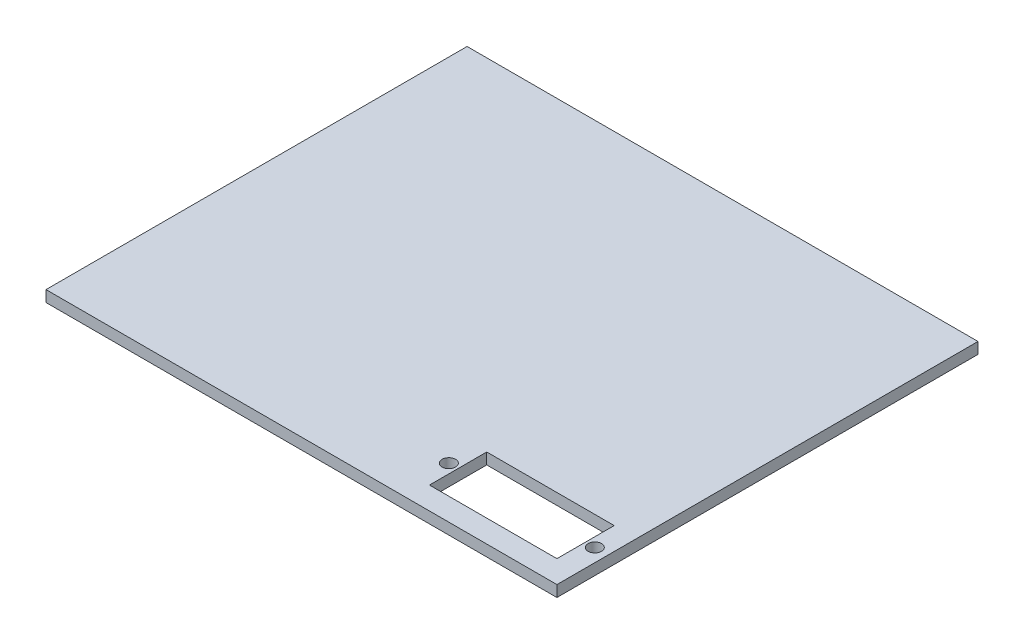
SolidWorks part; units mm, degrees
ref_plane "前视基准面" through (0, 0, 0) normal (0, 0, 1) x (1, 0, 0)
ref_plane "上视基准面" through (0, 0, 0) normal (0, 1, 0) x (1, 0, 0)
ref_plane "右视基准面" through (0, 0, 0) normal (1, 0, 0) x (0, 0, -1)
sketch "草图1" plane through (0, 0, 0) normal (0, 1, 0) x (1, 0, 0)
  line L1 (-45.5, 37.5) -> (45.5, 37.5)
  line L2 (-45.5, 37.5) -> (-45.5, -37.5)
  line L3 (-45.5, -37.5) -> (45.5, -37.5)
  line L4 (45.5, 37.5) -> (45.5, -37.5)
  line L5 (-45.5, 37.5) -> (45.5, -37.5) construction
  line L6 (-45.5, -37.5) -> (45.5, 37.5) construction
  point P0 (0, 0)
  dimension "D1" = 75
  dimension "D2" = 91
extrude "凸台-拉伸1" add sketch "草图1" along normal blind 2
ref_plane "基准面1" through (0, 2, 0) normal (0, 1, 0) x (1, 0, 0)
sketch "草图2" plane through (0, 2, 0) normal (0, 1, 0) x (1, 0, 0)
  line L0 (-45.5, -37.5) -> (45.5, -37.5) construction
  line L1 (18.8, -23.3) -> (41.5, -23.3)
  line L2 (18.8, -23.3) -> (18.8, -33.5)
  line L3 (18.8, -33.5) -> (41.5, -33.5)
  line L4 (41.5, -23.3) -> (41.5, -33.5)
  line L5 (45.5, -37.5) -> (45.5, 37.5) construction
  line L6 (30.15, -23.3) -> (30.15, -33.5) construction
  line L7 (30.15, -28.4) -> (17.15, -28.4) construction
  circle A0 centre (17.15, -28.4) radius 1.2
  circle A1 centre (43.15, -28.4) radius 1.2
  dimension "D6" = 2.4
  dimension "D1" = 22.7
  dimension "D2" = 10.2
  dimension "D3" = 4
  dimension "D4" = 4
  dimension "D5" = 13
extrude "切除-拉伸1" cut sketch "草图2" against normal blind 2
